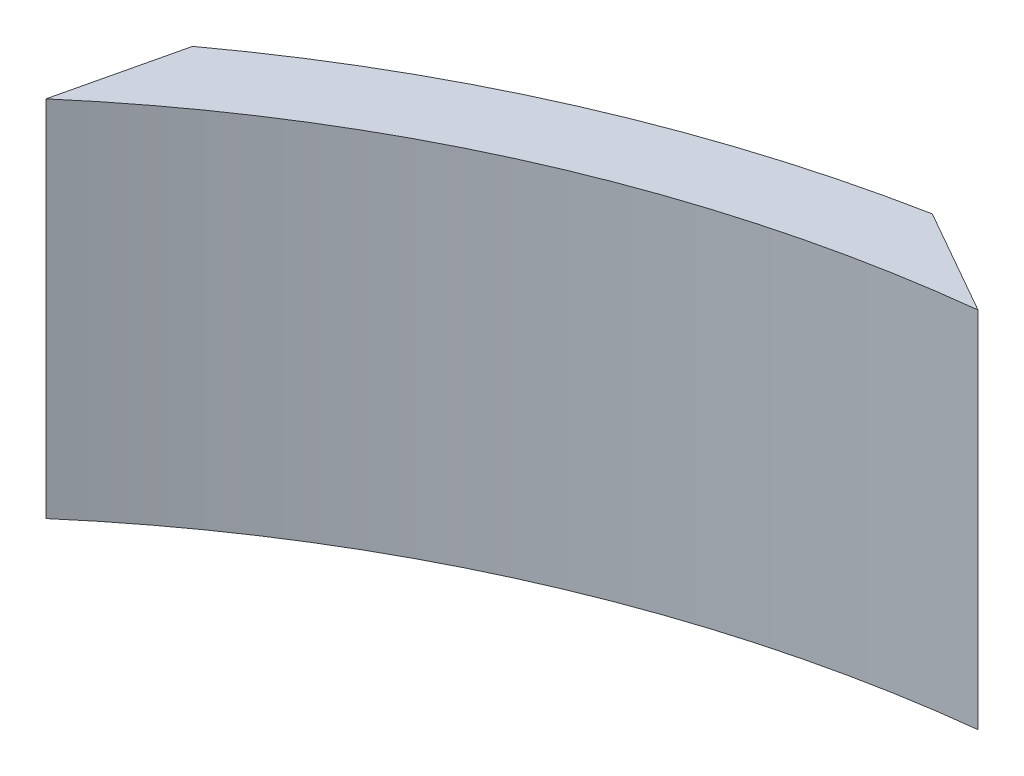
SolidWorks part; units mm, degrees
material "Porcelana cerâmica"
ref_plane "Plano frontal" through (0, 0, 0) normal (0, 0, 1) x (1, 0, 0)
ref_plane "Plano superior" through (0, 0, 0) normal (0, 1, 0) x (1, 0, 0)
ref_plane "Plano direito" through (0, 0, 0) normal (1, 0, 0) x (0, 0, -1)
sketch "Esboço1" plane through (0, 0, 0) normal (0, 1, 0) x (1, 0, 0)
  line L0 (0, 0) -> (0, 4) construction
  line L1 (0, 4) -> (-8, 8) construction
  line L2 (0, 8) -> (-8, 8) construction
  line L3 (-70, -23.5) -> (-70, -51.5) construction
  line L4 (-3.5, -3.5) -> (-14.3418, -3.5) construction
  line L5 (-53.013, -50.8344) -> (-52.0073, -63.6479) construction
  line L7 (-68.0936, -56.8666) -> (-59.985, -66.8389) construction
  line L8 (-56.4935, -68.5) -> (-9.8989, -68.5) construction
  line L9 (-21.2681, -16.5) -> (-38.2843, -16.5) construction
  line L10 (-17, 7.4893) -> (-24, 11.4723)
  line L11 (-58, -3.3682) -> (-59.8389, -11.2093)
  arc A0 (-8, 8) -> (-68.8228, -20.2773) centre (-8, -71.5519) ccw construction
  arc A1 (-68.8228, -20.2773) -> (-70, -23.5) centre (-65, -23.5) ccw construction
  arc A2 (0, 0) -> (-3.5, -3.5) centre (-3.5, 0) cw construction
  arc A3 (-3.5, -3.5) -> (-12.384, -10) centre (-3.5, -12.8212) ccw construction
  arc A4 (-12.384, -10) -> (-21.2681, -16.5) centre (-21.2681, -7.1788) cw construction
  arc A5 (-21.2681, -16.5) -> (-53.013, -50.8344) centre (-21.2681, -48.3426) ccw construction
  arc A6 (-52.0073, -63.6479) -> (-59.985, -66.8389) centre (-56.4935, -64) cw construction
  arc A7 (-53.013, -50.8344) -> (-70, -51.5) centre (-61.4935, -51.5) cw construction
  arc A8 (-70, -51.5) -> (-68.0936, -56.8666) centre (-61.4935, -51.5) ccw construction
  circle A9 centre (-61.4935, -51.5) radius 4.5 construction
  circle A10 centre (-56.4935, -64) radius 2 construction
  circle A11 centre (-45, -11.5) radius 3 construction
  arc A12 (-59.8389, -11.2093) -> (-17, 7.4893) centre (-8, -71.5519) cw
  arc A13 (-58, -3.3682) -> (-24, 11.4723) centre (-8, -71.5519) cw
  arc A14 (-55.0432, -7.4002) -> (-23.0538, 6.5627) centre (-8, -71.5519) cw construction
  dimension "D7" = 5
  dimension "D9" = 9
  dimension "D11" = 4
  dimension "D12" = 2.5
  dimension "D14" = 5
  dimension "D16" = 6
  dimension "D18" = 45
  dimension "D1" = 70
  dimension "D2" = 4
  dimension "D3" = 8
  dimension "D4" = 8
  dimension "D5" = 3.5
  dimension "D6" = 20
  dimension "D8" = 65
  dimension "D10" = 48
  dimension "D13" = 17
  dimension "D15" = 13
  dimension "D17" = 8
  dimension "D20" = 17
  dimension "D21" = 24
  dimension "D22" = 58
  dimension "D19" = 5
extrude "Ressalto-extrusão1" add sketch "Esboço1" along normal mid plane 24
